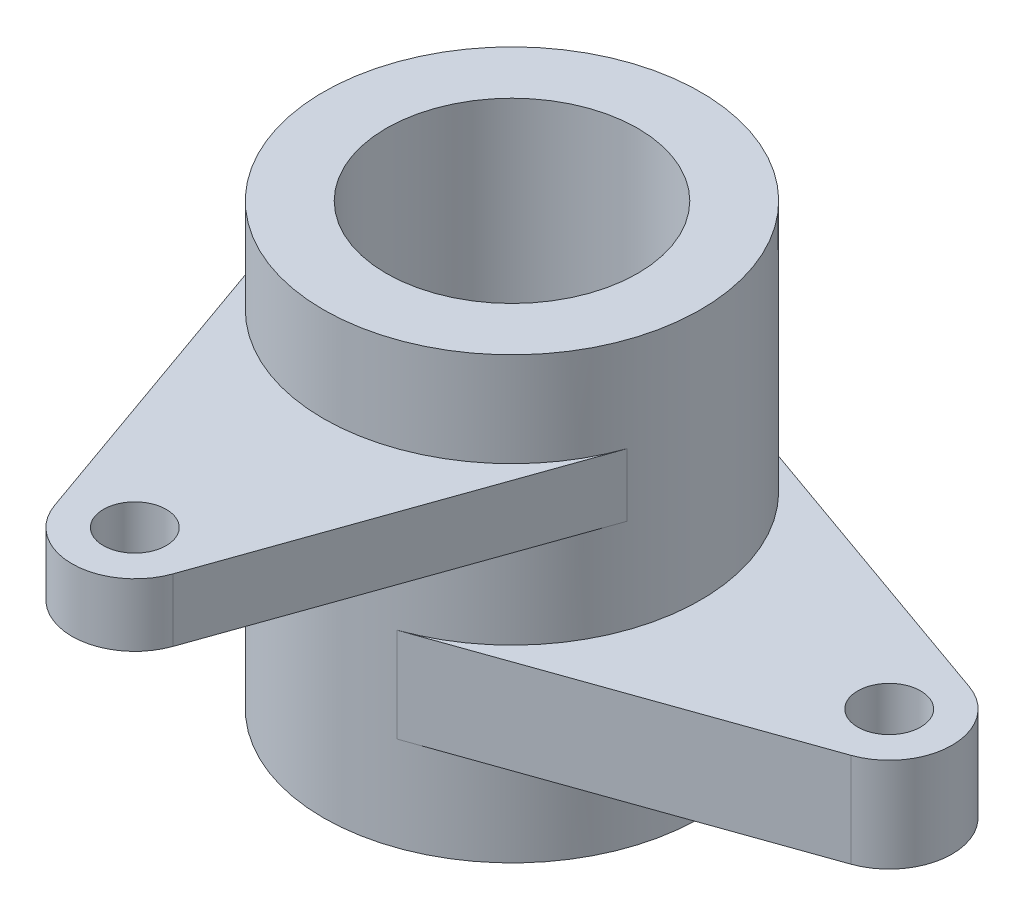
SolidWorks part; units mm, degrees
material "Hexcel AS4C (3000 Filaments)"
ref_plane "Front Plane" through (0, 0, 0) normal (0, 0, 1) x (1, 0, 0)
ref_plane "Top Plane" through (0, 0, 0) normal (0, 1, 0) x (1, 0, 0)
ref_plane "Right Plane" through (0, 0, 0) normal (1, 0, 0) x (0, 0, -1)
sketch "Sketch2" plane through (0, 0, 0) normal (0, 1, 0) x (1, 0, 0)
  circle A0 centre (0, 0) radius 30
  circle A1 centre (0, 0) radius 20
  dimension "D1" = 60
  dimension "D2" = 40
extrude "Boss-Extrude1" add sketch "Sketch2" along normal blind 70
ref_plane "Plane1" through (0, 15, 0) normal (0, 1, 0) x (1, 0, 0)
sketch "Sketch4" plane through (0, 15, 0) normal (0, 1, 0) x (1, 0, 0)
  line L0 (63.3333, 9.4281) -> (10, 28.2843)
  line L1 (63.3333, -9.4281) -> (10, -28.2843)
  line L2 (0, 0) -> (60, 0) construction
  arc A0 (63.3333, -9.4281) -> (63.3333, 9.4281) centre (60, 0) ccw
  circle A1 centre (60, 0) radius 5
  circle A2 centre (0, 0) radius 30 construction
  arc A3 (10, -28.2843) -> (10, 28.2843) centre (0, 0) ccw
  point P9 (0, 0)
  point P11 (0, 0)
  dimension "D1" = 20
  dimension "D2" = 10
  dimension "D3" = 60
extrude "Boss-Extrude2" add sketch "Sketch4" along normal blind 15
ref_plane "Plane2" through (0, 45, 0) normal (0, 1, 0) x (1, 0, 0)
sketch "Sketch5" plane through (0, 45, 0) normal (0, 1, 0) x (1, 0, 0)
  line L0 (0, 0) -> (0, -60) construction
  line L1 (-9.4281, -63.3333) -> (-28.2843, -10)
  line L2 (9.4281, -63.3333) -> (28.2843, -10)
  arc A0 (-9.4281, -63.3333) -> (9.4281, -63.3333) centre (0, -60) ccw
  circle A1 centre (0, -60) radius 5
  circle A2 centre (0, 0) radius 30 construction
  arc A3 (-28.2843, -10) -> (28.2843, -10) centre (0, 0) ccw
  point P12 (0, 0)
  point P13 (0, 0)
  dimension "D2" = 20
  dimension "D3" = 10
  dimension "D1" = 60
extrude "Boss-Extrude3" add sketch "Sketch5" along normal blind 10
